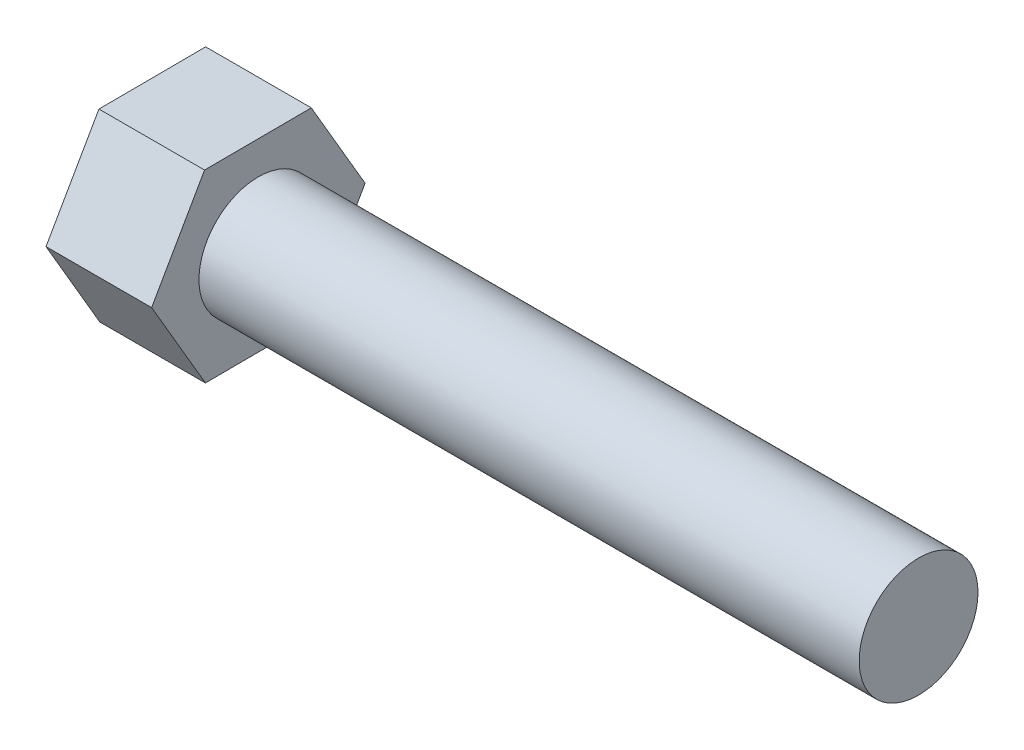
SolidWorks part; units mm, degrees
ref_plane "Front Plane" through (0, 0, 0) normal (0, 0, 1) x (1, 0, 0)
ref_plane "Top Plane" through (0, 0, 0) normal (0, 1, 0) x (1, 0, 0)
ref_plane "Right Plane" through (0, 0, 0) normal (1, 0, 0) x (0, 0, -1)
sketch "Sketch2" plane through (0, 0, 0) normal (1, 0, 0) x (0, 0, -1)
  line L1 (2.0374, -3.4903) -> (4.0414, 0.0193)
  line L2 (4.0414, 0.0193) -> (2.004, 3.5096)
  line L3 (2.004, 3.5096) -> (-2.0374, 3.4903)
  line L4 (-2.0374, 3.4903) -> (-4.0414, -0.0193)
  line L5 (-4.0414, -0.0193) -> (-2.004, -3.5096)
  line L6 (-2.004, -3.5096) -> (2.0374, -3.4903)
  circle A1 centre (0, 0) radius 3.5 construction
  dimension "D1" = 7
extrude "Boss-Extrude1" add sketch "Sketch2" along normal blind 4
sketch "Sketch3" plane through (4, 0, 0) normal (1, 0, 0) x (0, 0, -1)
  circle A0 centre (0, 0) radius 2.25
  dimension "D1" = 4.5
extrude "Boss-Extrude2" add sketch "Sketch3" along normal blind 25
